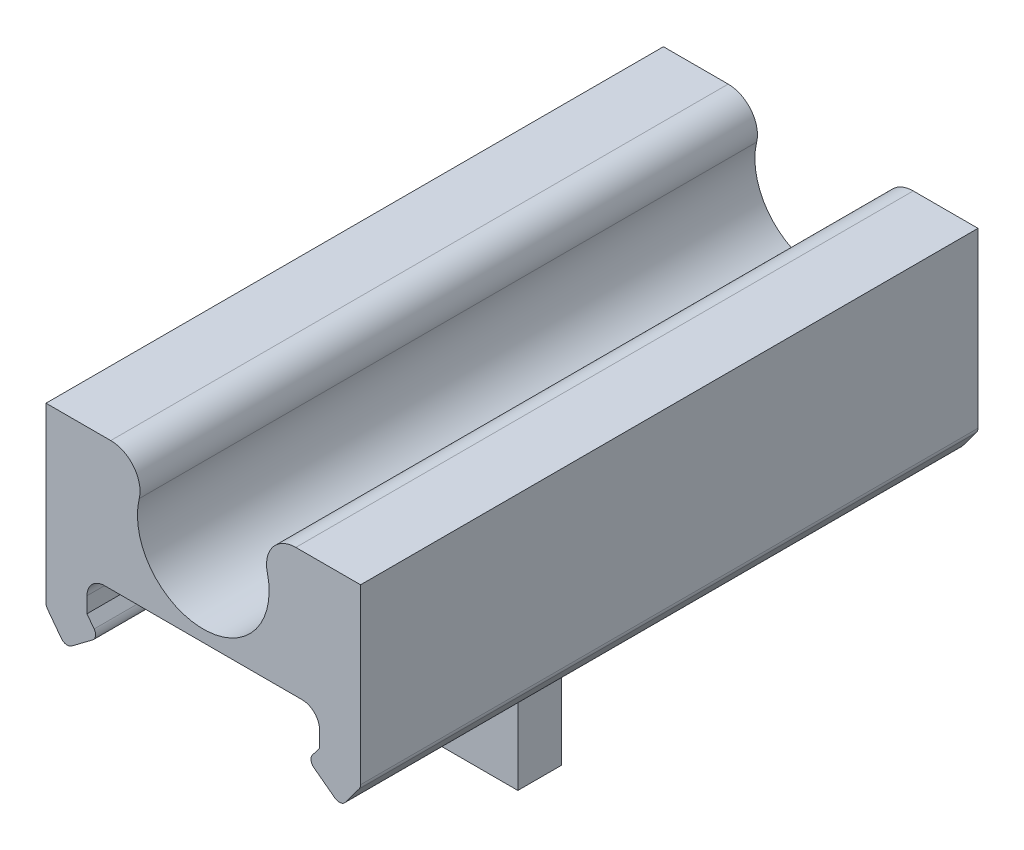
SolidWorks part; units mm, degrees
ref_plane "前视基准面" through (0, 0, 0) normal (0, 0, 1) x (1, 0, 0)
ref_plane "上视基准面" through (0, 0, 0) normal (0, 1, 0) x (1, 0, 0)
ref_plane "右视基准面" through (0, 0, 0) normal (1, 0, 0) x (0, 0, -1)
sketch "草图2" plane through (0, 0, 0) normal (0, 0, 1) x (1, 0, 0)
  line L0 (-12.25, 17.3) -> (-14.65, 15.5)
  line L1 (4.15, 15.5) -> (5.5, 17.3)
  line L2 (5.5, 17.3) -> (5.5, 22.3)
  line L3 (5.5, 22.3) -> (-16, 22.3)
  line L4 (-16, 22.3) -> (-16, 17.3)
  line L5 (-16, 17.3) -> (-14.65, 15.5)
  line L8 (-5.25, 11) -> (-5.25, 14.4674) construction
  line L9 (1.75, 17.3) -> (4.15, 15.5)
  line L10 (-16, 17.3) -> (-12.4, 12.5) construction
  line L11 (-10, 6) -> (-0.5, 6)
  line L12 (-10, 6) -> (-0.5, 6)
  line L15 (-0.5, 14.3) -> (2.5, 18.3)
  line L16 (2.5, 18.3) -> (2.5, 19.3)
  line L17 (1.5, 20.3) -> (-12, 20.3)
  line L18 (-13, 19.3) -> (-13, 18.3)
  line L19 (-13, 18.3) -> (-10, 14.3)
  line L20 (-10, 14.3) -> (-10, 6)
  line L25 (1.75, 17.3) -> (2.5, 18.3)
  line L26 (2.5, 18.3) -> (2.5, 19.3)
  line L28 (-13, 19.3) -> (-13, 18.3)
  line L29 (-13, 18.3) -> (-12.25, 17.3)
  line L30 (-13, 18.3) -> (-10, 14.3) construction
  line L31 (-0.5, 14.3) -> (2.5, 18.3) construction
  line L32 (1.9, 12.5) -> (5.5, 17.3) construction
  line L53 (2.5, 19.3) -> (-13, 19.3) construction
  line L54 (1.5, 20.3) -> (-12, 20.3)
  line L55 (-0.5, 6) -> (-0.5, 14.3)
  arc A4 (-12, 20.3) -> (-13, 19.3) centre (-12, 19.3) ccw
  arc A5 (-12, 20.3) -> (-13, 19.3) centre (-12, 19.3) ccw
  arc A6 (2.5, 19.3) -> (1.5, 20.3) centre (1.5, 19.3) ccw
  arc A7 (2.5, 19.3) -> (1.5, 20.3) centre (1.5, 19.3) ccw
  dimension "D3" = 1.25
  dimension "D1" = 0
  dimension "D2" = 3
extrude "凸台-拉伸1" add sketch "草图2" against normal up to surface (42.2 mm away) contours A7 L26 L25 L9 L1 L2 L3 L4 L5 L0 L29 L28 A5 L54
sketch "草图9" plane through (0, 0, -42.2) normal (0, 0, -1) x (-1, 0, 0)
  line L0 (-1.91, 17.18) -> (-2.7, 18.2333)
  line L1 (-2.7, 18.2333) -> (-2.7, 19.3)
  line L2 (-1.5, 20.5) -> (12, 20.5)
  line L3 (13.2, 19.3) -> (13.2, 18.2333)
  line L4 (13.2, 18.2333) -> (12.41, 17.18)
  line L12 (-1.5, 20.3) -> (12, 20.3)
  line L13 (13, 19.3) -> (13, 18.3)
  line L14 (13, 18.3) -> (12.25, 17.3)
  line L15 (12.25, 17.3) -> (14.65, 15.5)
  line L16 (14.65, 15.5) -> (16, 17.3)
  line L17 (16, 17.3) -> (16, 22.3)
  line L18 (16, 22.3) -> (-5.5, 22.3)
  line L19 (-5.5, 22.3) -> (-5.5, 17.3)
  line L20 (-5.5, 17.3) -> (-4.15, 15.5)
  line L21 (-4.15, 15.5) -> (-1.75, 17.3)
  line L22 (-1.75, 17.3) -> (-2.5, 18.3)
  line L23 (-2.5, 18.3) -> (-2.5, 19.3)
  line L24 (-1.5, 20.3) -> (12, 20.3)
  line L25 (13, 19.3) -> (13, 18.3)
  line L26 (13, 18.3) -> (12.25, 17.3)
  line L34 (-1.75, 17.3) -> (-2.5, 18.3)
  line L35 (-2.5, 18.3) -> (-2.5, 19.3)
  arc A0 (-1.5, 20.5) -> (-2.7, 19.3) centre (-1.5, 19.3) ccw
  arc A1 (13.2, 19.3) -> (12, 20.5) centre (12, 19.3) ccw
  arc A2 (13, 19.3) -> (12, 20.3) centre (12, 19.3) ccw
  arc A3 (-1.5, 20.3) -> (-2.5, 19.3) centre (-1.5, 19.3) ccw
  arc A4 (13, 19.3) -> (12, 20.3) centre (12, 19.3) ccw
  arc A5 (-1.5, 20.3) -> (-2.5, 19.3) centre (-1.5, 19.3) ccw
  line M15 (-1.5, 20.3) -> (12, 20.3)
  arc M16 (12, 20.3) -> (13, 19.3) centre (12, 19.3) cw
  line M17 (13, 19.3) -> (13, 18.3)
  line M18 (13, 18.3) -> (12.25, 17.3)
  line M19 (12.25, 17.3) -> (14.65, 15.5)
  line M25 (-4.15, 15.5) -> (-1.75, 17.3)
  line M26 (-1.75, 17.3) -> (-2.5, 18.3)
  line M27 (-2.5, 18.3) -> (-2.5, 19.3)
  arc M28 (-2.5, 19.3) -> (-1.5, 20.3) centre (-1.5, 19.3) cw
  dimension "D1" = 0
  dimension "D2" = 0.2
extrude "切除-拉伸5" cut sketch "草图9" against normal through all contours L3 A1 L2 A0 L1 L0 L4 M25 M26 M27 M28 M15 M16 M17 M18 M19
sketch "草图5" plane through (0, 20.5, 0) normal (0, -1, 0) x (1, 0, 0)
  line L0 (5.5, 0) -> (-16, 0) construction
  line L1 (-10.25, -16.5) -> (-0.25, -16.5)
  line L2 (-10.25, -16.5) -> (-10.25, -19.5)
  line L3 (-10.25, -19.5) -> (-0.25, -19.5)
  line L4 (-0.25, -16.5) -> (-0.25, -19.5)
  line L5 (-5.25, 0) -> (-5.25, -3.6969) construction
  line L8 (5.5, 0) -> (-16, 0) construction
  point P8 (-5.25, 0)
  point P9 (0, 0)
  point P10 (-5.25, -16.5)
  dimension "D1" = 10
  dimension "D2" = 3
  dimension "D3" = 16.5
extrude "凸台-拉伸4" add sketch "草图5" along normal blind 14.5
sketch "草图6" plane through (0, 22.3, 0) normal (0, 1, 0) x (1, 0, 0)
  line L4 (5.5, 42.2) -> (-16, 42.2)
  line L5 (-16, 42.2) -> (-16, 0)
  line L6 (-16, 0) -> (5.5, 0)
  line L7 (5.5, 0) -> (5.5, 42.2)
  line L8 (5.5, 42.2) -> (-16, 42.2)
  line L9 (-16, 42.2) -> (-16, 0)
  line L11 (5.5, 0) -> (5.5, 42.2)
  line L12 (-16, 0) -> (5.5, 0)
  dimension "D1" = 0
extrude "凸台-拉伸5" add sketch "草图6" along normal blind 7
sketch "草图7" plane through (0, 0, 0) normal (0, 0, 1) x (1, 0, 0)
  line L0 (-5.25, 29.3) -> (-5.25, 27.0872) construction
  line L1 (-16, 29.3) -> (5.5, 29.3) construction
  circle A0 centre (-5.25, 25.8) radius 4.5
  dimension "D1" = 9
  dimension "D2" = 3.5
extrude "切除-拉伸3" cut sketch "草图7" against normal up to surface (42.2 mm away) up to face at (-5.25, 19.6517, -42.2)
fillet "圆角2" radius 2 2 edges at (-8.0784, 29.3, -21.1) (-2.4216, 29.3, -21.1)
fillet "圆角3" radius 0.5 6 edges at (-16, 17.3, -21.1) (-14.65, 15.5, -21.1) (5.5, 17.3, -21.1) (4.15, 15.5, -21.1) (1.91, 17.18, -21.1) (-12.41, 17.18, -21.1)
equation "\"m\"= 2"
